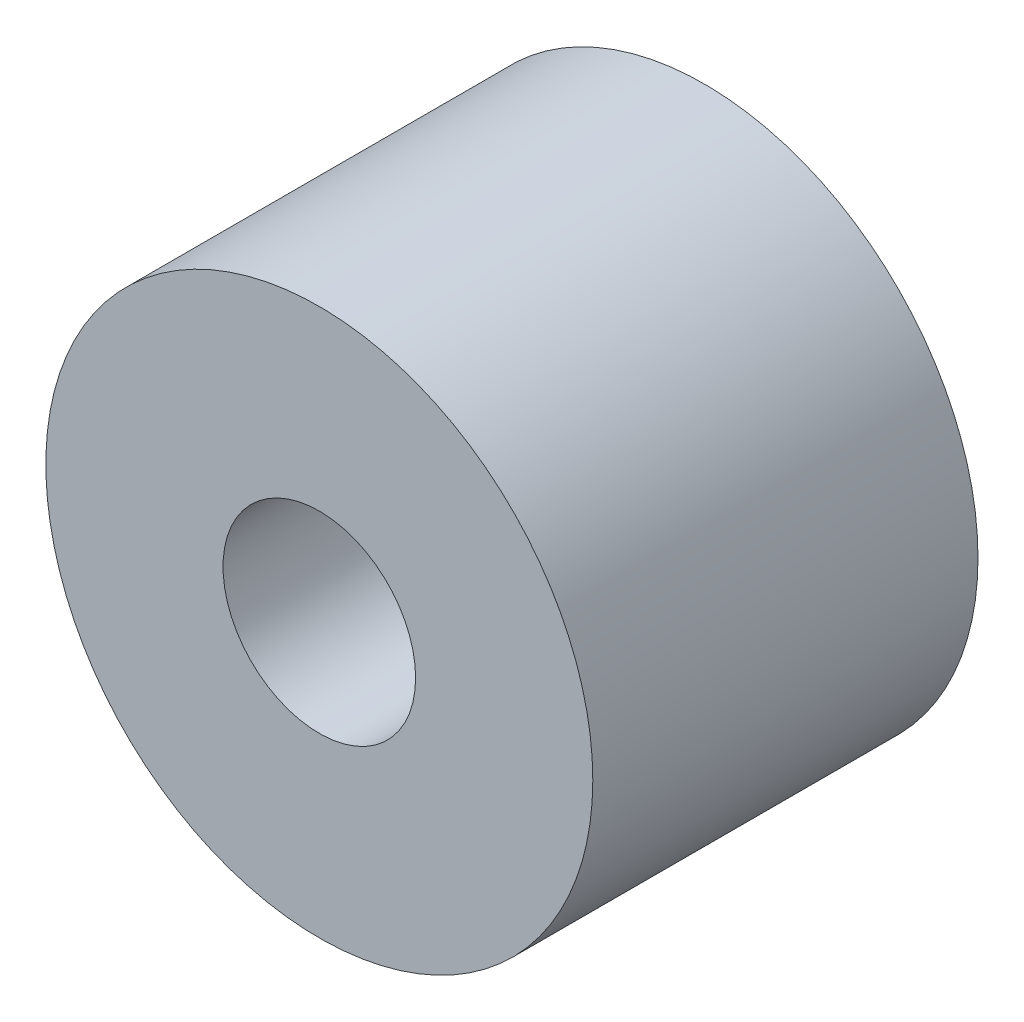
SolidWorks part; units mm, degrees
ref_plane "Front Plane" through (0, 0, 0) normal (0, 0, 1) x (1, 0, 0)
ref_plane "Top Plane" through (0, 0, 0) normal (0, 1, 0) x (1, 0, 0)
ref_plane "Right Plane" through (0, 0, 0) normal (1, 0, 0) x (0, 0, -1)
sketch "Sketch1" plane through (0, 0, 0) normal (0, 0, 1) x (1, 0, 0)
  circle A0 centre (0, 0) radius 14.2
  circle A1 centre (0, 0) radius 5
extrude "Connection_space_only_NO_THREADS_OR_SEALS" add sketch "Sketch1" along normal blind 20
